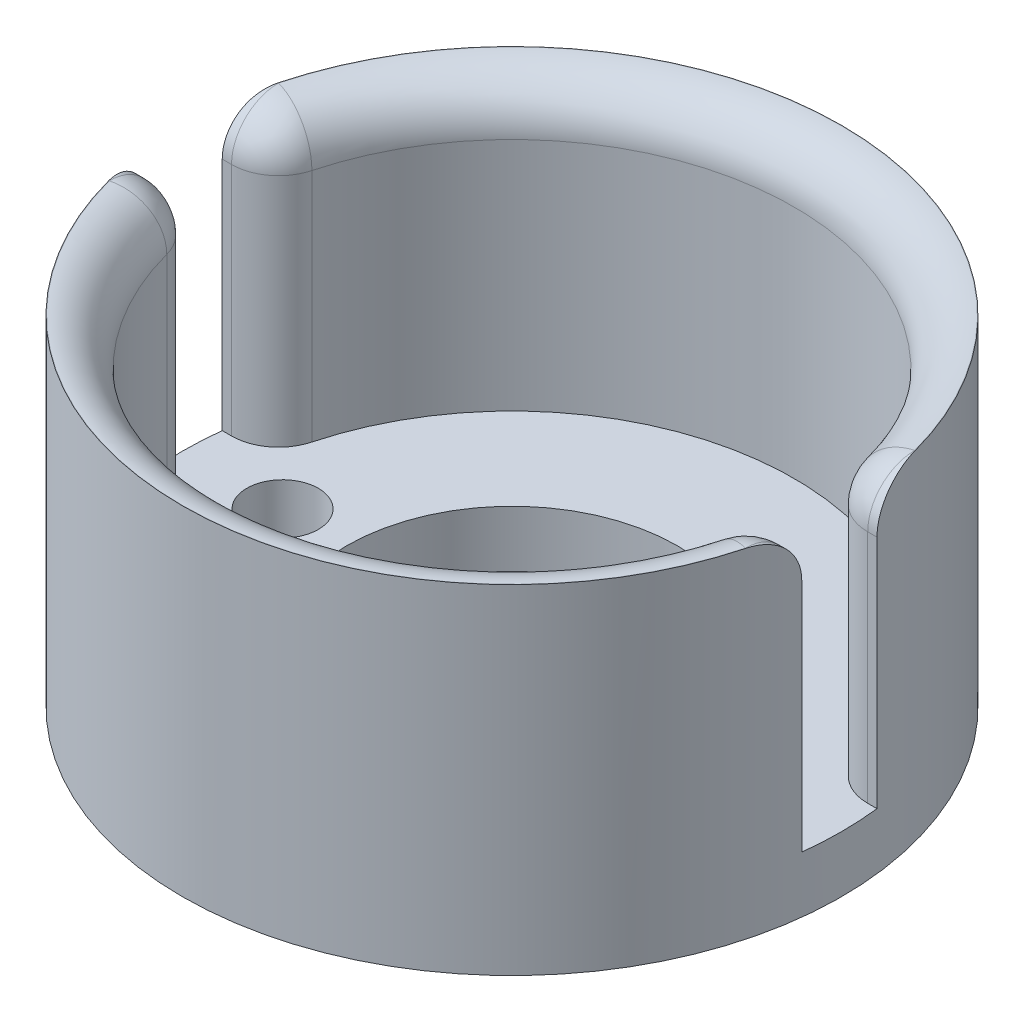
SolidWorks part; units mm, degrees
material "ABS"
ref_plane "Front Plane" through (0, 0, 0) normal (0, 0, 1) x (1, 0, 0)
ref_plane "Top Plane" through (0, 0, 0) normal (0, 1, 0) x (1, 0, 0)
ref_plane "Right Plane" through (0, 0, 0) normal (1, 0, 0) x (0, 0, -1)
sketch "Sketch1" plane through (0, 0, 0) normal (0, 1, 0) x (1, 0, 0)
  circle A0 centre (0, 0) radius 11.1252
  circle A1 centre (0, 0) radius 5.588
  circle A2 centre (-7.747, 0) radius 1.2065
  circle A3 centre (7.747, 0) radius 1.2065
  dimension "D1" = 22.2504
  dimension "D2" = 2.413
  dimension "D5" = 11.176
  dimension "D3" = 15.494
  dimension "D4" = 7.747
extrude "Boss-Extrude1" add sketch "Sketch1" along normal blind 1.905
sketch "Sketch2" plane through (0, 1.905, 0) normal (0, 1, 0) x (1, 0, 0)
  line L0 (-9.44, 1.27) -> (9.44, 1.27) construction
  line L1 (-9.44, -1.27) -> (9.44, -1.27) construction
  line L2 (-1000, 0) -> (49000, 0) construction
  line L3 (-9.44, 1.27) -> (-11.0525, 1.27)
  line L4 (9.44, 1.27) -> (11.0525, 1.27)
  line L5 (9.44, -1.27) -> (11.0525, -1.27)
  line L6 (-9.44, -1.27) -> (-11.0525, -1.27)
  arc A0 (9.44, 1.27) -> (-9.44, 1.27) centre (0, 0) ccw
  arc A1 (9.44, -1.27) -> (-9.44, -1.27) centre (0, 0) cw
  arc A3 (-11.0525, -1.27) -> (11.0525, -1.27) centre (0, 0) ccw
  arc A4 (11.0525, 1.27) -> (-11.0525, 1.27) centre (0, 0) ccw
  dimension "D1" = 9.525
  dimension "D3" = 22.2504
  dimension "D2" = 2.54
extrude "Boss-Extrude2" add sketch "Sketch2" along normal blind 9.525
fillet "Fillet1" radius 1.5875 10 edges at (10.2462, 11.43, 1.27) (10.2462, 11.43, -1.27) (-10.2462, 11.43, -1.27) (0, 11.43, -9.525) (0, 11.43, 9.525) (-10.2462, 11.43, 1.27) (9.44, 6.6675, -1.27) (-9.44, 6.6675, -1.27) (-9.44, 6.6675, 1.27) (9.44, 6.6675, 1.27)
